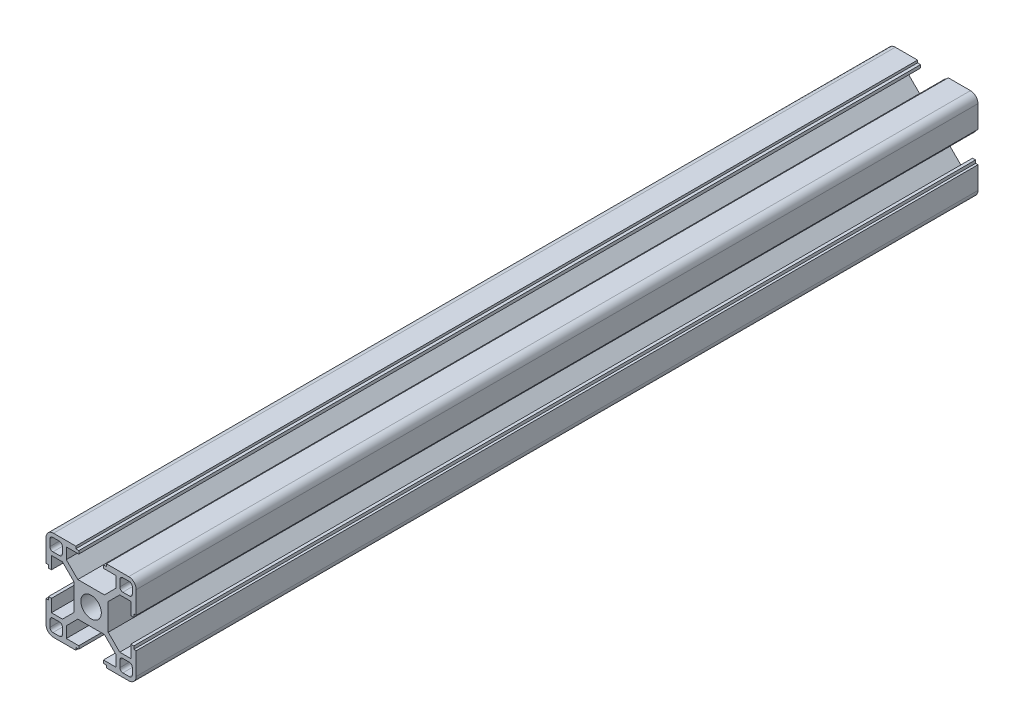
SolidWorks part; units mm, degrees
material "6061-T6 (SS)"
ref_plane "前视基准面" through (0, 0, 0) normal (0, 0, 1) x (1, 0, 0)
ref_plane "上视基准面" through (0, 0, 0) normal (0, 1, 0) x (1, 0, 0)
ref_plane "右视基准面" through (0, 0, 0) normal (1, 0, 0) x (0, 0, -1)
sketch "Sketch1" plane through (0, 0, 0) normal (0, 0, 1) x (1, 0, 0)
  line L0 (-5.1, 15) -> (-5.1, 14.2)
  line L1 (-12.5, -15) -> (12.5, -15)
  line L2 (-15, -12.5) -> (-15, 12.5)
  line L3 (-12.5, 15) -> (12.5, 15)
  line L4 (15, -12.5) -> (15, 12.5)
  line L5 (-15, -15) -> (15, 15) construction
  line L6 (-15, 15) -> (15, -15) construction
  line L7 (-5.1, 14.2) -> (-4.1, 14.2)
  line L8 (-4.1, 14.2) -> (-4.1, 13.2)
  line L9 (-4.1, 13.2) -> (-8.25, 13.2)
  line L10 (-8.25, 13.2) -> (-8.25, 9.5228)
  line L11 (-8.25, 9.5228) -> (-4.4272, 5.7)
  line L12 (-4.4272, 5.7) -> (4.4272, 5.7)
  line L13 (-5.1, 15) -> (5.1, 15)
  line L14 (0, 15) -> (0, 5.7) construction
  line L15 (8.25, 9.5228) -> (4.4272, 5.7)
  line L16 (8.25, 13.2) -> (8.25, 9.5228)
  line L17 (4.1, 13.2) -> (8.25, 13.2)
  line L18 (4.1, 14.2) -> (4.1, 13.2)
  line L19 (5.1, 14.2) -> (4.1, 14.2)
  line L20 (5.1, 15) -> (5.1, 14.2)
  line L21 (15, 5.1) -> (14.2, 5.1)
  line L22 (14.2, 5.1) -> (14.2, 4.1)
  line L23 (14.2, 4.1) -> (13.2, 4.1)
  line L24 (13.2, 4.1) -> (13.2, 8.25)
  line L25 (13.2, 8.25) -> (9.5228, 8.25)
  line L26 (9.5228, 8.25) -> (5.7, 4.4272)
  line L27 (5.7, 4.4272) -> (5.7, -4.4272)
  line L28 (15, 5.1) -> (15, -5.1)
  line L29 (9.5228, -8.25) -> (5.7, -4.4272)
  line L30 (13.2, -8.25) -> (9.5228, -8.25)
  line L31 (13.2, -4.1) -> (13.2, -8.25)
  line L32 (14.2, -4.1) -> (13.2, -4.1)
  line L33 (14.2, -5.1) -> (14.2, -4.1)
  line L34 (15, -5.1) -> (14.2, -5.1)
  line L35 (15, 0) -> (5.7, 0) construction
  line L36 (5.1, -15) -> (5.1, -14.2)
  line L37 (5.1, -14.2) -> (4.1, -14.2)
  line L38 (4.1, -14.2) -> (4.1, -13.2)
  line L39 (4.1, -13.2) -> (8.25, -13.2)
  line L40 (8.25, -13.2) -> (8.25, -9.5228)
  line L41 (8.25, -9.5228) -> (4.4272, -5.7)
  line L42 (4.4272, -5.7) -> (-4.4272, -5.7)
  line L43 (5.1, -15) -> (-5.1, -15)
  line L44 (-8.25, -9.5228) -> (-4.4272, -5.7)
  line L45 (-8.25, -13.2) -> (-8.25, -9.5228)
  line L46 (-4.1, -13.2) -> (-8.25, -13.2)
  line L47 (-4.1, -14.2) -> (-4.1, -13.2)
  line L48 (-5.1, -14.2) -> (-4.1, -14.2)
  line L49 (-5.1, -15) -> (-5.1, -14.2)
  line L50 (0, -15) -> (0, -5.7) construction
  line L51 (-15, -5.1) -> (-14.2, -5.1)
  line L52 (-14.2, -5.1) -> (-14.2, -4.1)
  line L53 (-14.2, -4.1) -> (-13.2, -4.1)
  line L54 (-13.2, -4.1) -> (-13.2, -8.25)
  line L55 (-13.2, -8.25) -> (-9.5228, -8.25)
  line L56 (-9.5228, -8.25) -> (-5.7, -4.4272)
  line L57 (-5.7, -4.4272) -> (-5.7, 4.4272)
  line L58 (-15, -5.1) -> (-15, 5.1)
  line L59 (-9.5228, 8.25) -> (-5.7, 4.4272)
  line L60 (-13.2, 8.25) -> (-9.5228, 8.25)
  line L61 (-13.2, 4.1) -> (-13.2, 8.25)
  line L62 (-14.2, 4.1) -> (-13.2, 4.1)
  line L63 (-14.2, 5.1) -> (-14.2, 4.1)
  line L64 (-15, 5.1) -> (-14.2, 5.1)
  line L65 (-15, 0) -> (-5.7, 0) construction
  line L66 (0, 0) -> (0, 5.7) construction
  circle A0 centre (0, 0) radius 3.4
  arc A1 (-12.5, -15) -> (-15, -12.5) centre (-12.5, -12.5) cw
  arc A2 (12.5, -15) -> (15, -12.5) centre (12.5, -12.5) ccw
  arc A3 (12.5, 15) -> (15, 12.5) centre (12.5, 12.5) cw
  arc A4 (-15, 12.5) -> (-12.5, 15) centre (-12.5, 12.5) cw
  point P0 (0, 0)
  dimension "D3" = 6.8
  dimension "D12" = 2.5
  dimension "D1" = 30
  dimension "D2" = 30
  dimension "D4" = 16.5
  dimension "D5" = 8.2
  dimension "D6" = 10.2
  dimension "D7" = 7.5
  dimension "D9" = 1.8
  dimension "D10" = 1.8
  dimension "D11" = 0.8
  dimension "D8" = 4
extrude "Extrude1" add sketch "Sketch1" along normal blind 280 contours A4 L2 L64 L63 L62 L61 L60 L59 L57 L56 L55 L54 L53 L52 L51 A1 L1 L49 L48 L47 L46 L45 L44 L42 L41 L40 L39 L38 L37 L36 A2 L4 L34 L33 L32 L31 L30 L29 L27 L26 L25 L24 L23 L22 L21 A3 L3 L20
sketch "Sketch2" plane through (0, 0, 280) normal (0, 0, 1) x (1, 0, 0)
  line L0 (13.7, 12.7) -> (13.7, 10.55)
  line L1 (-12.7, 13.7) -> (-10.55, 13.7)
  line L2 (-13.7, 12.7) -> (-13.7, 10.55)
  line L3 (-12.7, 9.55) -> (-10.55, 9.55)
  line L4 (-9.55, 12.7) -> (-9.55, 10.55)
  line L5 (-13.7, 13.7) -> (-9.55, 9.55) construction
  line L6 (-13.7, 9.55) -> (-9.55, 13.7) construction
  line L7 (12.7, 13.7) -> (10.55, 13.7)
  line L8 (9.55, 12.7) -> (9.55, 10.55)
  line L9 (12.7, 9.55) -> (10.55, 9.55)
  line L10 (12.7, -13.7) -> (10.55, -13.7)
  line L11 (13.7, -12.7) -> (13.7, -10.55)
  line L12 (12.7, -9.55) -> (10.55, -9.55)
  line L13 (9.55, -12.7) -> (9.55, -10.55)
  line L14 (-13.7, -12.7) -> (-13.7, -10.55)
  line L15 (-12.7, -13.7) -> (-10.55, -13.7)
  line L16 (-9.55, -12.7) -> (-9.55, -10.55)
  line L17 (-12.7, -9.55) -> (-10.55, -9.55)
  line L18 (0, 0) -> (-9.55, 9.55) construction
  line L19 (-12.5, 15) -> (-5.1, 15) construction
  line L20 (-15, 5.1) -> (-15, 12.5) construction
  line L21 (-13.2, 8.25) -> (-9.5228, 8.25) construction
  line L22 (-8.25, 13.2) -> (-8.25, 9.5228) construction
  arc A0 (-13.7, -12.7) -> (-12.7, -13.7) centre (-12.7, -12.7) ccw
  arc A1 (-10.55, -13.7) -> (-9.55, -12.7) centre (-10.55, -12.7) ccw
  arc A2 (-9.55, -10.55) -> (-10.55, -9.55) centre (-10.55, -10.55) ccw
  arc A3 (-13.7, -10.55) -> (-12.7, -9.55) centre (-12.7, -10.55) cw
  arc A4 (13.7, -10.55) -> (12.7, -9.55) centre (12.7, -10.55) ccw
  arc A5 (12.7, -13.7) -> (13.7, -12.7) centre (12.7, -12.7) ccw
  arc A6 (10.55, -13.7) -> (9.55, -12.7) centre (10.55, -12.7) cw
  arc A7 (10.55, -9.55) -> (9.55, -10.55) centre (10.55, -10.55) ccw
  arc A8 (13.7, 12.7) -> (12.7, 13.7) centre (12.7, 12.7) ccw
  arc A9 (13.7, 10.55) -> (12.7, 9.55) centre (12.7, 10.55) cw
  arc A10 (9.55, 10.55) -> (10.55, 9.55) centre (10.55, 10.55) ccw
  arc A11 (10.55, 13.7) -> (9.55, 12.7) centre (10.55, 12.7) ccw
  arc A12 (-10.55, 13.7) -> (-9.55, 12.7) centre (-10.55, 12.7) cw
  arc A13 (-10.55, 9.55) -> (-9.55, 10.55) centre (-10.55, 10.55) ccw
  arc A14 (-13.7, 10.55) -> (-12.7, 9.55) centre (-12.7, 10.55) ccw
  arc A15 (-12.7, 13.7) -> (-13.7, 12.7) centre (-12.7, 12.7) ccw
  point P0 (-11.625, 11.625)
  dimension "D2" = 1
  dimension "D3" = 1.3
  dimension "D4" = 1.3
  dimension "D5" = 1.3
  dimension "D6" = 1.3
  dimension "D1" = 4
extrude "Extrude2" cut sketch "Sketch2" against normal through all
